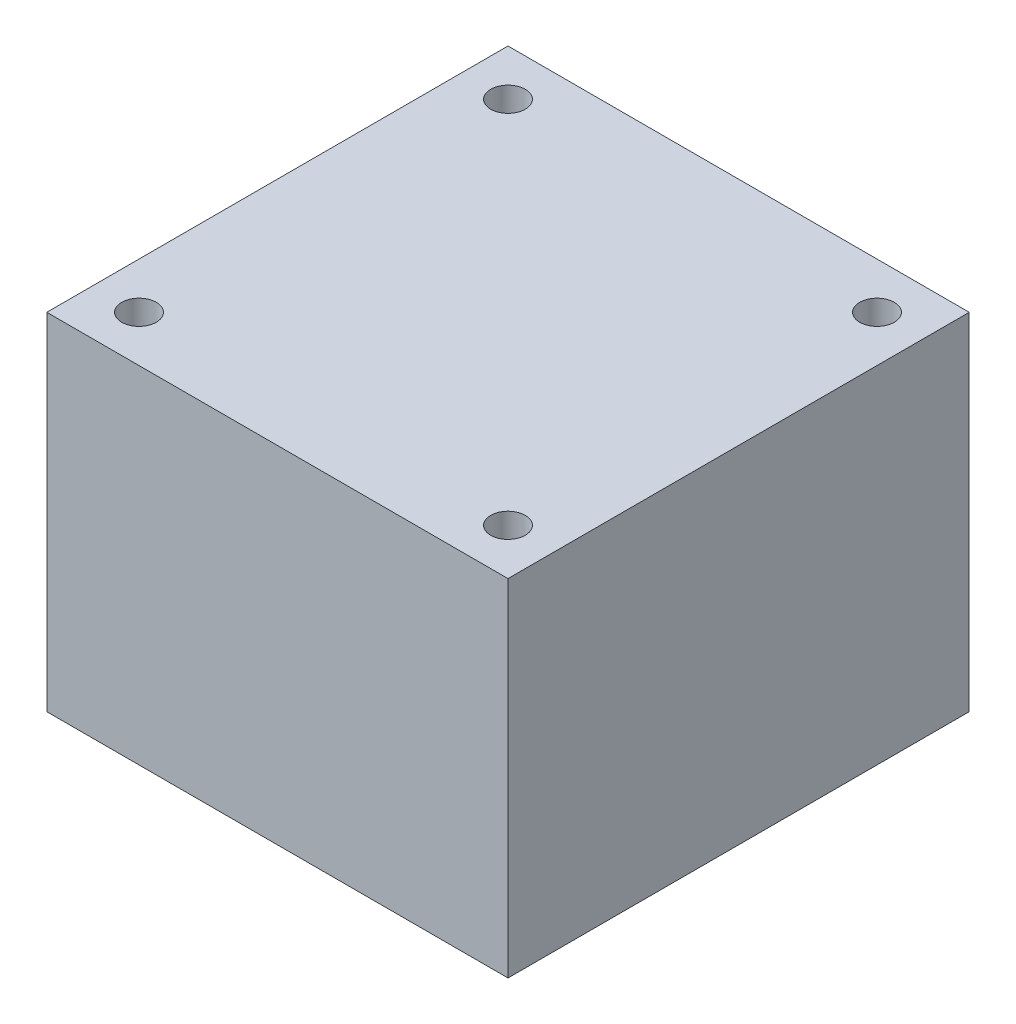
SolidWorks part; units mm, degrees
ref_plane "前视基准面" through (0, 0, 0) normal (0, 0, 1) x (1, 0, 0)
ref_plane "上视基准面" through (0, 0, 0) normal (0, 1, 0) x (1, 0, 0)
ref_plane "右视基准面" through (0, 0, 0) normal (1, 0, 0) x (0, 0, -1)
sketch "草图1" plane through (0, 0, 0) normal (0, 1, 0) x (1, 0, 0)
  line L1 (-20, 20) -> (20, 20)
  line L2 (-20, 20) -> (-20, -20)
  line L3 (-20, -20) -> (20, -20)
  line L4 (20, 20) -> (20, -20)
  line L5 (-20, 20) -> (20, -20) construction
  line L6 (-20, -20) -> (20, 20) construction
  point P0 (0, 0)
  dimension "D1" = 40
  dimension "D2" = 40
extrude "凸台-拉伸1" add sketch "草图1" along normal blind 30
sketch "草图2" plane through (0, 30, 0) normal (0, 1, 0) x (1, 0, 0)
  line L0 (-16, 16) -> (16, 16) construction
  line L1 (16, 16) -> (16, -16) construction
  line L2 (16, -16) -> (-16, -16) construction
  line L3 (-16, -16) -> (-16, 16) construction
  line L4 (0, -20) -> (0, -16) construction
  line L5 (-20, -20) -> (20, -20) construction
  line L6 (-20, 0) -> (-16, 0) construction
  line L7 (-20, 20) -> (-20, -20) construction
  circle A0 centre (-16, 16) radius 1.5
  circle A1 centre (16, 16) radius 1.5
  circle A2 centre (16, -16) radius 1.5
  circle A3 centre (-16, -16) radius 1.5
  dimension "D1" = 3
  dimension "D2" = 32
extrude "切除-拉伸1" cut sketch "草图2" against normal through all
